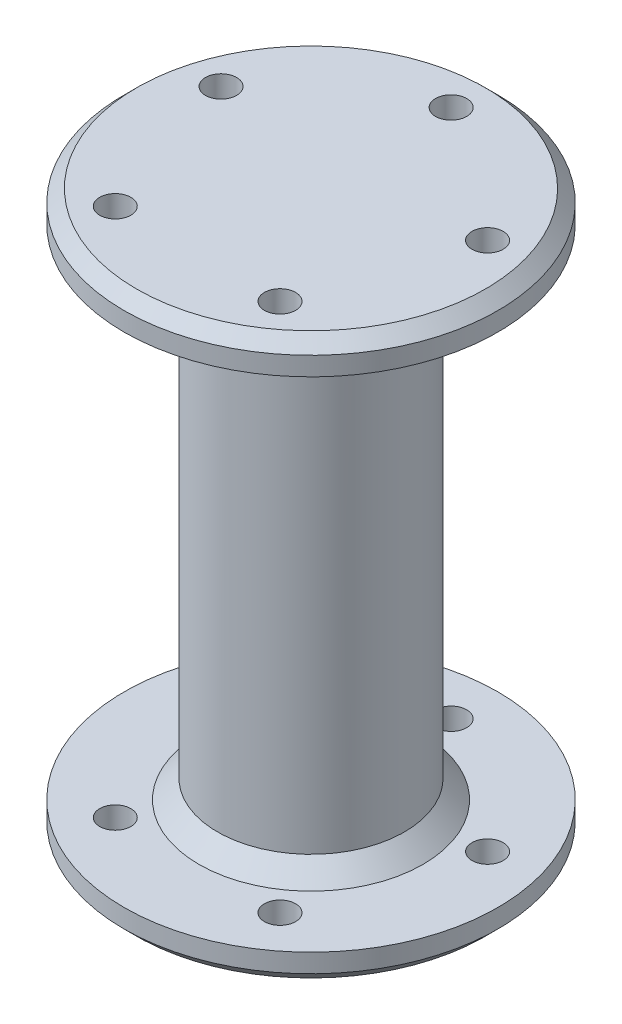
SolidWorks part; units mm, degrees
ref_plane "Front Plane" through (0, 0, 0) normal (0, 0, 1) x (1, 0, 0)
ref_plane "Top Plane" through (0, 0, 0) normal (0, 1, 0) x (1, 0, 0)
ref_plane "Right Plane" through (0, 0, 0) normal (1, 0, 0) x (0, 0, -1)
sketch "Sketch1" plane through (0, 0, 0) normal (0, 1, 0) x (1, 0, 0)
  circle A0 centre (0, 0) radius 15
  dimension "ShaftDiameter" = 30
extrude "Boss-Extrude1" add sketch "Sketch1" along normal mid plane 80
sketch "Sketch4" plane through (0, 40, 0) normal (0, 1, 0) x (1, 0, 0)
  circle A0 centre (0, 0) radius 30
  dimension "capdiameter" = 60
extrude "Boss-Extrude2" add sketch "Sketch4" along normal blind 5 contours A0
chamfer "Chamfer1" distance 2 angle 45 1 edges at (0, 45, 30)
sketch "Sketch6" plane through (0, 45, 0) normal (0, 1, 0) x (1, 0, 0)
  line L0 (0, 15) -> (0, 30) construction
  circle A0 centre (0, 0) radius 15 construction
  circle A1 centre (0, 0) radius 30 construction
  circle A2 centre (0, 22.5) radius 2.5
  dimension "D" = 5
extrude "Cut-Extrude1" cut sketch "Sketch6" against normal through all
pattern_circular "CirPattern1" count 5 over 360 about axis through (0, 0, 0) along (0, 1, 0) of "Cut-Extrude1"
hole_wizard "CBORE for #12 Binding Head Machine Screw1" positions "3DSketch1" profile "Sketch7" counterbore size "#12" standard "ANSI Inch"
sketch3d "3DSketch1"
  point P0 (0, 0, 0)
  point P3 (0, 0, 0)
  point P5 (0, 0, 0)
  point P7 (-0.6964, 45, 0.4858)
  point P9 (0, 0, 0)
sketch "Sketch7" plane through (-0.6964, 45, 0.4858) normal (1, 0, 0) x (0, 0, 1)
  line L0 (0, 0) -> (0, 90)
  line L1 (0, 90) -> (2.8956, 90)
  line L3 (2.8956, 90) -> (2.8956, 3.5814)
  line L4 (5.9538, 3.5814) -> (2.8956, 3.5814)
  line L5 (5.9538, 3.5814) -> (5.9538, 0.635)
  line L6 (5.9538, 0.635) -> (6.5888, 0)
  line L7 (6.5888, 0) -> (0, 0)
  line L8 (-5.9538, 0.635) -> (-6.5888, 0) construction
  line L11 (0, -6.35) -> (0, 107.95) construction
  dimension "CapDiameter" = 5.7912
  dimension "Thru Hole Depth" = 90
  dimension "C'Bore Dia." = 11.9075
  dimension "C'Bore Depth" = 3.5814
  dimension "CapDiameter." = 13.1775
  dimension "Near C'Sink Angle" = 90
chamfer "Chamfer2" distance 3 angle 45 1 edges at (0, 40, 15)
mirror "Mirror1" about plane through (0, 0, 0) normal (0, 1, 0) of "CBORE for #12 Binding Head Machine Screw1", "CirPattern1", "Chamfer2", "Boss-Extrude2", "Chamfer1"
